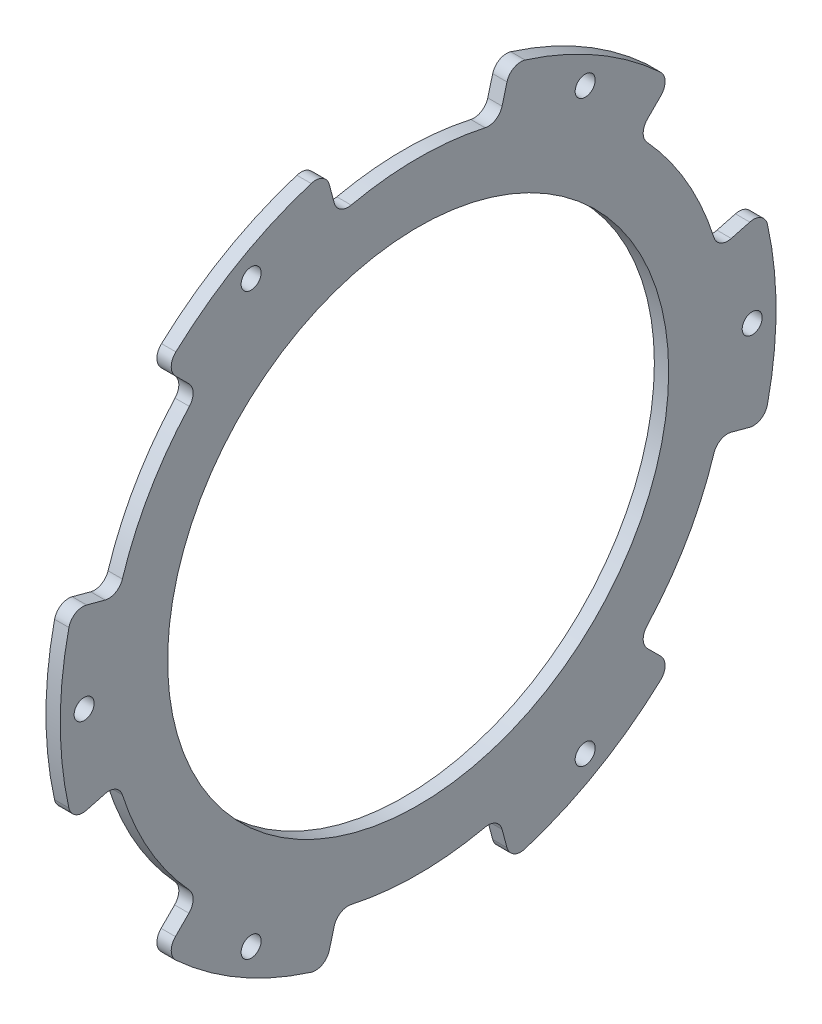
SolidWorks part; units mm, degrees
material "Thornel Mat VMA"
ref_plane "前视基准面" through (0, 0, 0) normal (0, 0, 1) x (1, 0, 0)
ref_plane "上视基准面" through (0, 0, 0) normal (0, 1, 0) x (1, 0, 0)
ref_plane "右视基准面" through (0, 0, 0) normal (1, 0, 0) x (0, 0, -1)
other "Configuration Table"
sketch "草图2" plane through (0, 0, 0) normal (1, 0, 0) x (0, 0, -1)
  line B0 (-60.4152, 26.957) -> (-57.5842, 24.1259)
  line B1 (-75.1668, -6.3279) -> (-79.034, -5.2917)
  line B2 (-79.034, -42.5293) -> (-75.1668, -41.4931)
  line B3 (-57.5842, -71.947) -> (-60.4152, -74.778)
  line B4 (-28.1665, -93.3968) -> (-27.1303, -89.5295)
  line B5 (8.0348, -89.5295) -> (9.071, -93.3968)
  line B6 (41.3197, -74.778) -> (38.4887, -71.947)
  line B7 (56.0713, -41.4931) -> (59.9385, -42.5293)
  line B8 (59.9385, -5.2917) -> (56.0713, -6.3279)
  line B9 (38.4887, 24.1259) -> (41.3197, 26.957)
  line B10 (9.071, 45.5758) -> (8.0348, 41.7085)
  line B11 (-27.1303, 41.7085) -> (-28.1665, 45.5758)
  circle B12 centre (-44.5478, 36.7113) radius 2.8071
  circle B13 centre (-79.5478, -23.9105) radius 2.8071
  circle B14 centre (-44.5478, -84.5323) radius 2.8071
  circle B15 centre (25.4522, -84.5323) radius 2.8071
  circle B16 centre (60.4522, -23.9105) radius 2.8071
  circle B17 centre (25.4522, 36.7113) radius 2.8071
  arc B18 (-31.9608, 47.6622) -> (-60.325, 31.2862) centre (-9.5478, -23.9105) ccw
  arc B19 (-60.325, 31.2862) -> (-60.4152, 26.957) centre (-58.2939, 29.0783) ccw
  arc B20 (-57.4927, 19.979) -> (-57.5842, 24.1259) centre (-59.7055, 22.0046) ccw
  arc B21 (-57.4927, 19.979) -> (-71.5296, -4.3337) centre (-9.5478, -23.9105) ccw
  arc B22 (-75.1668, -6.3279) -> (-71.5296, -4.3337) centre (-74.3903, -3.4302) ccw
  arc B23 (-79.034, -5.2917) -> (-82.7381, -7.5345) centre (-79.8105, -8.1895) ccw
  arc B24 (-82.7381, -7.5345) -> (-82.7381, -40.2866) centre (-9.5478, -23.9105) ccw
  arc B25 (-82.7381, -40.2866) -> (-79.034, -42.5293) centre (-79.8105, -39.6315) ccw
  arc B26 (-71.5296, -43.4873) -> (-75.1668, -41.4931) centre (-74.3903, -44.3908) ccw
  arc B27 (-71.5296, -43.4873) -> (-57.4927, -67.8) centre (-9.5478, -23.9105) ccw
  arc B28 (-57.5842, -71.947) -> (-57.4927, -67.8) centre (-59.7055, -69.8256) ccw
  arc B29 (-60.4152, -74.778) -> (-60.325, -79.1072) centre (-58.2939, -76.8993) ccw
  arc B30 (-60.325, -79.1072) -> (-31.9608, -95.4832) centre (-9.5478, -23.9105) ccw
  arc B31 (-31.9608, -95.4832) -> (-28.1665, -93.3968) centre (-31.0643, -92.6203) ccw
  arc B32 (-23.5847, -87.3768) -> (-27.1303, -89.5295) centre (-24.2325, -90.306) ccw
  arc B33 (-23.5847, -87.3768) -> (4.4892, -87.3768) centre (-9.5478, -23.9105) ccw
  arc B34 (8.0348, -89.5295) -> (4.4892, -87.3768) centre (5.137, -90.306) ccw
  arc B35 (9.071, -93.3968) -> (12.8653, -95.4832) centre (11.9688, -92.6203) ccw
  arc B36 (12.8653, -95.4832) -> (41.2295, -79.1072) centre (-9.5478, -23.9105) ccw
  arc B37 (41.2295, -79.1072) -> (41.3197, -74.778) centre (39.1984, -76.8993) ccw
  arc B38 (38.3972, -67.8) -> (38.4887, -71.947) centre (40.61, -69.8256) ccw
  arc B39 (38.3972, -67.8) -> (52.4341, -43.4873) centre (-9.5478, -23.9105) ccw
  arc B40 (56.0713, -41.4931) -> (52.4341, -43.4873) centre (55.2948, -44.3908) ccw
  arc B41 (59.9385, -42.5293) -> (63.6426, -40.2866) centre (60.715, -39.6315) ccw
  arc B42 (63.6426, -40.2866) -> (63.6426, -7.5345) centre (-9.5478, -23.9105) ccw
  arc B43 (63.6426, -7.5345) -> (59.9385, -5.2917) centre (60.715, -8.1895) ccw
  arc B44 (52.4341, -4.3337) -> (56.0713, -6.3279) centre (55.2948, -3.4302) ccw
  arc B45 (52.4341, -4.3337) -> (38.3972, 19.979) centre (-9.5478, -23.9105) ccw
  arc B46 (38.4887, 24.1259) -> (38.3972, 19.979) centre (40.61, 22.0046) ccw
  arc B47 (41.3197, 26.957) -> (41.2295, 31.2862) centre (39.1984, 29.0783) ccw
  arc B48 (41.2295, 31.2862) -> (12.8653, 47.6622) centre (-9.5478, -23.9105) ccw
  arc B49 (12.8653, 47.6622) -> (9.071, 45.5758) centre (11.9688, 44.7993) ccw
  arc B50 (4.4892, 39.5557) -> (8.0348, 41.7085) centre (5.137, 42.485) ccw
  arc B51 (4.4892, 39.5557) -> (-23.5847, 39.5557) centre (-9.5478, -23.9105) ccw
  arc B52 (-27.1303, 41.7085) -> (-23.5847, 39.5557) centre (-24.2325, 42.485) ccw
  arc B53 (-28.1665, 45.5758) -> (-31.9608, 47.6622) centre (-31.0643, 44.7993) ccw
sketch_block_instance "块2-1"
sketch_block "块2"
extrude "凸台-拉伸2" add sketch "草图2" along normal blind 3
sketch "草图3" plane through (3, 0, 0) normal (1, 0, 0) x (0, 0, -1)
  circle A0 centre (-9.5478, -23.9105) radius 52.5
  dimension "D1" = 105
extrude "切除-拉伸1" cut sketch "草图3" against normal blind 3
sketch "草图4" plane through (3, 0, 0) normal (1, 0, 0) x (0, 0, -1)
  circle A0 centre (-44.5478, 36.7113) radius 2.8071
  circle A1 centre (-44.5478, 36.7113) radius 2.1
  dimension "D1" = 5.6143
  dimension "D2" = 4.2
extrude "凸台-拉伸3" add sketch "草图4" against normal up to surface (3 mm away) up to face at (0, -23.9105, -42.9522)
pattern_circular "阵列(圆周)1" count 6 over 360 about axis through (0, -23.9105, 9.5478) along (1, 0, 0) of "凸台-拉伸3"
